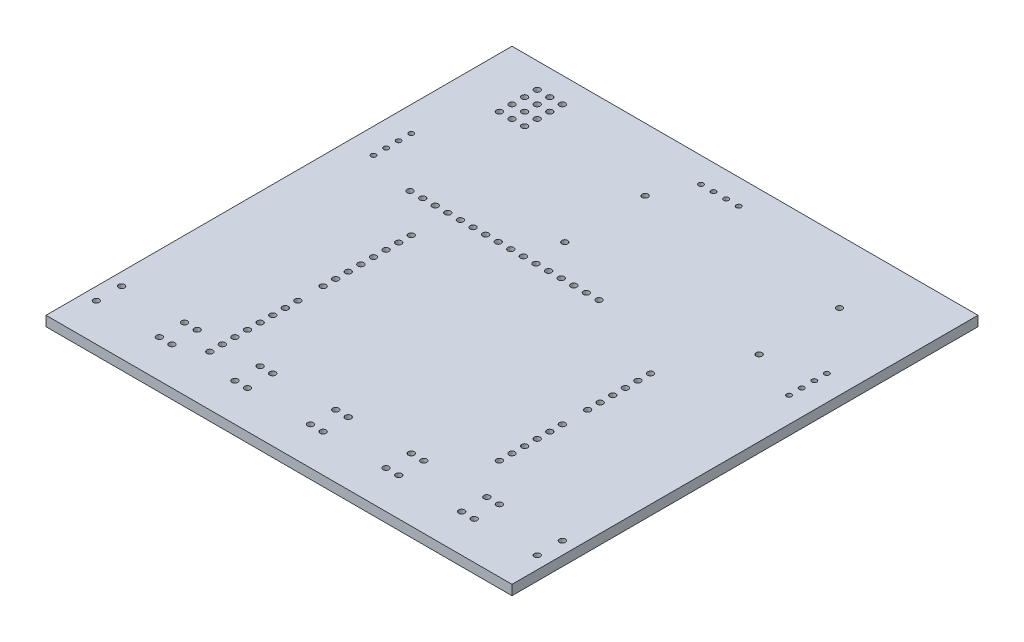
SolidWorks part; units mm, degrees
ref_plane "Front Plane" through (0, 0, 0) normal (0, 0, 1) x (1, 0, 0)
ref_plane "Top Plane" through (0, 0, 0) normal (0, 1, 0) x (1, 0, 0)
ref_plane "Right Plane" through (0, 0, 0) normal (1, 0, 0) x (0, 0, -1)
sketch "Sketch1" plane through (0, 0, 0) normal (0, 1, 0) x (1, 0, 0)
  line L0 (46.99, 93.98) -> (46.99, 0) construction
  line L1 (0, 0) -> (93.98, 0)
  line L2 (0, 0) -> (0, 93.98)
  line L3 (0, 93.98) -> (93.98, 93.98)
  line L4 (93.98, 0) -> (93.98, 93.98)
  line L5 (0, 46.99) -> (93.98, 46.99) construction
  line L6 (93.98, 93.98) -> (73.98, 93.98) construction
  line L7 (0, 78.98) -> (20, 78.98) construction
  line L8 (0, 78.98) -> (0, 93.98) construction
  line L9 (0, 93.98) -> (20, 93.98) construction
  line L10 (20, 78.98) -> (20, 93.98) construction
  line L11 (73.98, 78.98) -> (73.98, 93.98) construction
  line L12 (93.98, 78.98) -> (73.98, 78.98) construction
  line L13 (93.98, 78.98) -> (93.98, 93.98) construction
  dimension "D1" = 93.98
  dimension "D2" = 93.98
  dimension "D3" = 15
  dimension "D4" = 20
extrude "Boss-Extrude1" add sketch "Sketch1" along normal blind 2 contours L4 L12 L11 L3 L10 L7 L2 L1
sketch "Sketch2" plane through (0, 2, 0) normal (0, 1, 0) x (1, 0, 0)
  line L0 (46.99, 93.98) -> (46.99, 0) construction
  line L1 (0, 93.98) -> (93.98, 93.98) construction
  line L2 (0, 0) -> (93.98, 0) construction
  line L3 (22.86, 50.8) -> (22.86, 10.16) construction
  line L4 (71.12, 50.8) -> (71.12, 20.32) construction
  line L5 (22.86, 50.8) -> (71.12, 50.8) construction
  circle A0 centre (22.86, 50.8) radius 0.6
  circle A1 centre (22.86, 48.26) radius 0.6
  circle A2 centre (22.86, 45.72) radius 0.6
  circle A3 centre (22.86, 43.18) radius 0.6
  circle A4 centre (22.86, 40.64) radius 0.6
  circle A5 centre (22.86, 38.1) radius 0.6
  circle A6 centre (22.86, 35.56) radius 0.6
  circle A7 centre (22.86, 33.02) radius 0.6
  circle A8 centre (22.86, 27.94) radius 0.6
  circle A9 centre (22.86, 25.4) radius 0.6
  circle A10 centre (22.86, 22.86) radius 0.6
  circle A11 centre (22.86, 20.32) radius 0.6
  circle A12 centre (22.86, 17.78) radius 0.6
  circle A13 centre (22.86, 15.24) radius 0.6
  circle A14 centre (22.86, 12.7) radius 0.6
  circle A15 centre (22.86, 10.16) radius 0.6
  circle A16 centre (71.12, 50.8) radius 0.6
  circle A17 centre (71.12, 48.26) radius 0.6
  circle A18 centre (71.12, 45.72) radius 0.6
  circle A19 centre (71.12, 43.18) radius 0.6
  circle A20 centre (71.12, 40.64) radius 0.6
  circle A21 centre (71.12, 38.1) radius 0.6
  circle A22 centre (71.12, 33.02) radius 0.6
  circle A23 centre (71.12, 30.48) radius 0.6
  circle A24 centre (71.12, 27.94) radius 0.6
  circle A25 centre (71.12, 25.4) radius 0.6
  circle A26 centre (71.12, 22.86) radius 0.6
  circle A27 centre (71.12, 20.32) radius 0.6
  point P62 (46.99, 50.8)
  dimension "D1" = 1.2
  dimension "D3" = 1.2
  dimension "D5" = 1.2
  dimension "D7" = 1.2
  dimension "D9" = 5.08
  dimension "D10" = 5.08
  dimension "D11" = 48.26
  dimension "D12" = 40.64
  dimension "D13" = 30.48
  dimension "D14" = 10.16
  dimension "D2" = 8
  dimension "D4" = 8
  dimension "D6" = 6
  dimension "D8" = 6
extrude "Cut-Extrude1" cut sketch "Sketch2" against normal through all
sketch "Sketch3" plane through (0, 0, 0) normal (0, -1, 0) x (1, 0, 0)
  line L0 (0, 0) -> (0, -93.98) construction
  line L2 (53.1, -58.42) -> (15, -58.42) construction
  line L5 (0, 0) -> (93.98, 0) construction
  circle A0 centre (15, -58.42) radius 0.6
  circle A1 centre (17.54, -58.42) radius 0.6
  circle A2 centre (20.08, -58.42) radius 0.6
  circle A3 centre (22.62, -58.42) radius 0.6
  circle A4 centre (25.16, -58.42) radius 0.6
  circle A5 centre (27.7, -58.42) radius 0.6
  circle A6 centre (30.24, -58.42) radius 0.6
  circle A7 centre (32.78, -58.42) radius 0.6
  circle A8 centre (35.32, -58.42) radius 0.6
  circle A9 centre (37.86, -58.42) radius 0.6
  circle A10 centre (40.4, -58.42) radius 0.6
  circle A11 centre (42.94, -58.42) radius 0.6
  circle A12 centre (45.48, -58.42) radius 0.6
  circle A13 centre (48.02, -58.42) radius 0.6
  circle A14 centre (50.56, -58.42) radius 0.6
  circle A15 centre (53.1, -58.42) radius 0.6
  dimension "D1" = 1.2
  dimension "D3" = 15
  dimension "D4" = 58.42
  dimension "D5" = 38.1
  dimension "D2" = 16
extrude "Cut-Extrude2" cut sketch "Sketch3" against normal through all
sketch "Sketch4" plane through (0, 0, 0) normal (0, -1, 0) x (1, 0, 0)
  line L0 (46.99, 0) -> (46.99, -93.98) construction
  line L1 (0, 0) -> (93.98, 0) construction
  line L2 (0, -93.98) -> (93.98, -93.98) construction
  line L4 (5.08, -60.96) -> (5.08, -68.58) construction
  line L5 (50.8, -88.9) -> (43.18, -88.9) construction
  line L6 (0, -93.98) -> (93.98, -93.98) construction
  line L7 (0, 0) -> (0, -93.98) construction
  line L8 (0, 0) -> (93.98, 0) construction
  circle A0 centre (5.08, -60.96) radius 0.5
  circle A1 centre (5.08, -63.5) radius 0.5
  circle A2 centre (5.08, -66.04) radius 0.5
  circle A3 centre (5.08, -68.58) radius 0.5
  circle A4 centre (88.9, -68.58) radius 0.5
  circle A5 centre (88.9, -66.04) radius 0.5
  circle A6 centre (88.9, -63.5) radius 0.5
  circle A7 centre (88.9, -60.96) radius 0.5
  circle A8 centre (43.18, -88.9) radius 0.5
  circle A9 centre (45.72, -88.9) radius 0.5
  circle A10 centre (48.26, -88.9) radius 0.5
  circle A11 centre (50.8, -88.9) radius 0.5
  point P34 (46.99, -88.9)
  dimension "D1" = 1
  dimension "D2" = 5.08
  dimension "D3" = 68.58
  dimension "D6" = 1
  dimension "D7" = 5.08
  dimension "D5" = 7.62
  dimension "D10" = 7.62
  dimension "D4" = 4
  dimension "D9" = 4
extrude "Cut-Extrude3" cut sketch "Sketch4" against normal through all
sketch "Sketch5" plane through (0, 2, 0) normal (0, 1, 0) x (1, 0, 0)
  line L2 (93.98, 0) -> (93.98, 93.98) construction
  line L3 (78.74, 81.28) -> (39.54, 81.28) construction
  line L4 (78.74, 81.28) -> (78.74, 65.08) construction
  line L5 (78.74, 65.08) -> (39.54, 65.08) construction
  line L6 (39.54, 81.28) -> (39.54, 65.08) construction
  line L7 (0, 93.98) -> (93.98, 93.98) construction
  circle A0 centre (78.74, 81.28) radius 0.6
  circle A1 centre (39.54, 81.28) radius 0.6
  circle A2 centre (39.54, 65.08) radius 0.6
  circle A3 centre (78.74, 65.08) radius 0.6
  dimension "D1" = 1.2
  dimension "D3" = 12.7
  dimension "D2" = 15.24
  dimension "D6" = 39.2
  dimension "D7" = 16.2
  dimension "D4" = 2
  dimension "D5" = 2
extrude "Cut-Extrude4" cut sketch "Sketch5" against normal through all
sketch "Sketch6" plane through (0, 2, 0) normal (0, 1, 0) x (1, 0, 0)
  line L0 (0, 93.98) -> (93.98, 93.98) construction
  line L1 (0, 0) -> (0, 93.98) construction
  line L2 (10.16, 88.9) -> (15.24, 88.9) construction
  line L3 (15.24, 88.9) -> (15.24, 81.28) construction
  line L4 (15.24, 81.28) -> (10.16, 81.28) construction
  line L5 (10.16, 81.28) -> (10.16, 88.9) construction
  circle A0 centre (10.16, 88.9) radius 0.6
  circle A1 centre (12.7, 88.9) radius 0.6
  circle A2 centre (15.24, 88.9) radius 0.6
  circle A3 centre (12.7, 86.36) radius 0.6
  circle A4 centre (15.24, 86.36) radius 0.6
  circle A5 centre (12.7, 83.82) radius 0.6
  circle A6 centre (15.24, 83.82) radius 0.6
  circle A7 centre (12.7, 81.28) radius 0.6
  circle A8 centre (15.24, 81.28) radius 0.6
  circle A9 centre (10.16, 86.36) radius 0.6
  circle A10 centre (10.16, 83.82) radius 0.6
  circle A11 centre (10.16, 81.28) radius 0.6
  dimension "D1" = 1.2
  dimension "D2" = 5.08
  dimension "D3" = 10.16
  dimension "D6" = 7.62
  dimension "D7" = 5.08
  dimension "D4" = 3
  dimension "D5" = 4
extrude "Cut-Extrude5" cut sketch "Sketch6" against normal blind 10
sketch "Sketch7" plane through (0, 2, 0) normal (0, 1, 0) x (1, 0, 0)
  line L0 (0, 0) -> (93.98, 0) construction
  line L1 (2.54, 5.08) -> (15.24, 5.08) construction
  line L2 (2.54, 5.08) -> (2.54, 17.78) construction
  line L3 (2.54, 17.78) -> (15.24, 17.78) construction
  line L4 (15.24, 5.08) -> (15.24, 17.78) construction
  line L5 (17.78, 5.08) -> (30.48, 5.08) construction
  line L6 (17.78, 5.08) -> (17.78, 17.78) construction
  line L7 (17.78, 17.78) -> (30.48, 17.78) construction
  line L8 (30.48, 5.08) -> (30.48, 17.78) construction
  line L11 (33.02, 5.08) -> (45.72, 5.08) construction
  line L12 (33.02, 5.08) -> (33.02, 17.78) construction
  line L13 (33.02, 17.78) -> (45.72, 17.78) construction
  line L14 (45.72, 5.08) -> (45.72, 17.78) construction
  line L15 (48.26, 5.08) -> (60.96, 5.08) construction
  line L16 (48.26, 5.08) -> (48.26, 17.78) construction
  line L17 (48.26, 17.78) -> (60.96, 17.78) construction
  line L18 (60.96, 5.08) -> (60.96, 17.78) construction
  line L19 (63.5, 5.08) -> (76.2, 5.08) construction
  line L20 (63.5, 5.08) -> (63.5, 17.78) construction
  line L21 (63.5, 17.78) -> (76.2, 17.78) construction
  line L22 (76.2, 5.08) -> (76.2, 17.78) construction
  line L23 (78.74, 5.08) -> (91.44, 5.08) construction
  line L24 (78.74, 5.08) -> (78.74, 17.78) construction
  line L25 (78.74, 17.78) -> (91.44, 17.78) construction
  line L26 (91.44, 5.08) -> (91.44, 17.78) construction
  line L27 (2.54, 11.43) -> (91.44, 11.43) construction
  circle A0 centre (15.24, 12.7) radius 0.6
  circle A1 centre (15.24, 7.62) radius 0.6
  circle A2 centre (2.54, 12.7) radius 0.6
  circle A3 centre (2.54, 7.62) radius 0.6
  circle A4 centre (30.48, 12.7) radius 0.6
  circle A5 centre (30.48, 7.62) radius 0.6
  circle A6 centre (17.78, 12.7) radius 0.6
  circle A7 centre (17.78, 7.62) radius 0.6
  circle A8 centre (45.72, 12.7) radius 0.6
  circle A9 centre (45.72, 7.62) radius 0.6
  circle A10 centre (33.02, 12.7) radius 0.6
  circle A11 centre (33.02, 7.62) radius 0.6
  circle A12 centre (60.96, 12.7) radius 0.6
  circle A13 centre (60.96, 7.62) radius 0.6
  circle A14 centre (48.26, 12.7) radius 0.6
  circle A15 centre (48.26, 7.62) radius 0.6
  circle A16 centre (76.2, 12.7) radius 0.6
  circle A17 centre (76.2, 7.62) radius 0.6
  circle A18 centre (63.5, 12.7) radius 0.6
  circle A19 centre (63.5, 7.62) radius 0.6
  circle A20 centre (91.44, 12.7) radius 0.6
  circle A21 centre (91.44, 7.62) radius 0.6
  circle A22 centre (78.74, 12.7) radius 0.6
  circle A23 centre (78.74, 7.62) radius 0.6
  dimension "D3" = 1.2
  dimension "D1" = 5.08
  dimension "D4" = 2.54
  dimension "D5" = 5.08
  dimension "D9" = 88.9
  dimension "D8" = 6
extrude "Cut-Extrude6" cut sketch "Sketch7" against normal through all
